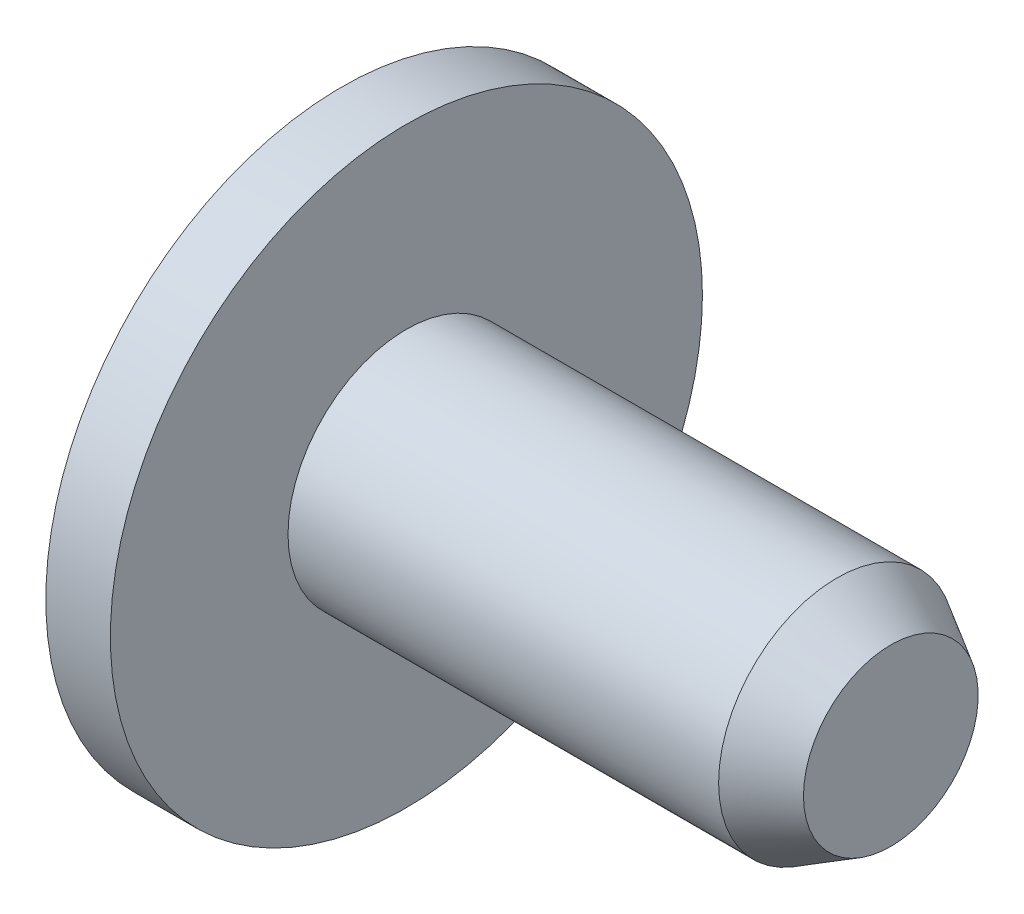
SolidWorks part; units mm, degrees
material "Acier non allié"
ref_plane "Plan de face" through (0, 0, 0) normal (0, 0, 1) x (1, 0, 0)
ref_plane "Plan de dessus" through (0, 0, 0) normal (0, 1, 0) x (1, 0, 0)
ref_plane "Plan de droite" through (0, 0, 0) normal (1, 0, 0) x (0, 0, -1)
sketch "Esquisse1" plane through (0, 0, 0) normal (0, 0, 1) x (1, 0, 0)
  line L0 (-2.1823, 0) -> (7.1997, 0) construction
  line L1 (0, 1.1) -> (0, 2.05)
  line L2 (0, 2.05) -> (-0.8, 1.8356)
  line L3 (0, 1.1) -> (4, 1.1)
  line L4 (4, 1.1) -> (4.5, 0.8113)
  line L5 (4.5, 0.8113) -> (4.5, 0)
  line L6 (4.5, 0) -> (-1.6, 0)
  arc A0 (-0.8, 1.8356) -> (-1.6, 0) centre (0.906, 0) ccw
  point P3 (4.5, 0.4057)
  point P10 (0, 1.575)
  dimension "D1" = 2.2
  dimension "D2" = 4.5
  dimension "D3" = 30
  dimension "D4" = 0.5
  dimension "D5" = 1.6
  dimension "D6" = 15
  dimension "D7" = 0.8
  dimension "D8" = 4.1
revolve "Révolution1" add sketch "Esquisse1" angle 360 about L0
cosmetic thread "Représentation de filetage1" parameters "D2"=1.693
sketch "Esquisse2" plane through (0, 0, 0) normal (0, 0, 1) x (1, 0, 0)
  line L1 (-1.2, -0.2) -> (-1.6, -0.2)
  line L2 (-1.2, -0.2) -> (-1.2, 0.2)
  line L3 (-1.2, 0.2) -> (-1.6, 0.2)
  line L4 (-1.6, -0.2) -> (-1.6, 0.2)
  line L5 (-1.2, -0.2) -> (-1.6, 0.2) construction
  line L6 (-1.2, 0.2) -> (-1.6, -0.2) construction
  arc A0 (-0.8, 1.8356) -> (-0.8, -1.8356) centre (0.906, 0) ccw construction
  point P0 (-1.4, 0)
  dimension "D1" = 0.4
  dimension "D2" = 0.4
extrude "Enlèv. mat.-Extru.1" cut sketch "Esquisse2" against normal through all both and the other way through all
pattern_circular "Répétition circulaire1" count 2 over 90 about axis through (-2.1823, 0, 0) along (-1, 0, 0) of "Enlèv. mat.-Extru.1"
sketch "Esquisse3" plane through (0, 0, 0) normal (1, 0, 0) x (0, 0, -1)
  circle A0 centre (0, 0) radius 2.75
  dimension "D1" = 5.5
extrude "Boss.-Extru.1" add sketch "Esquisse3" against normal blind 0.6
equation "\"D7@Esquisse1\"=\"D5@Esquisse1\"/2"
